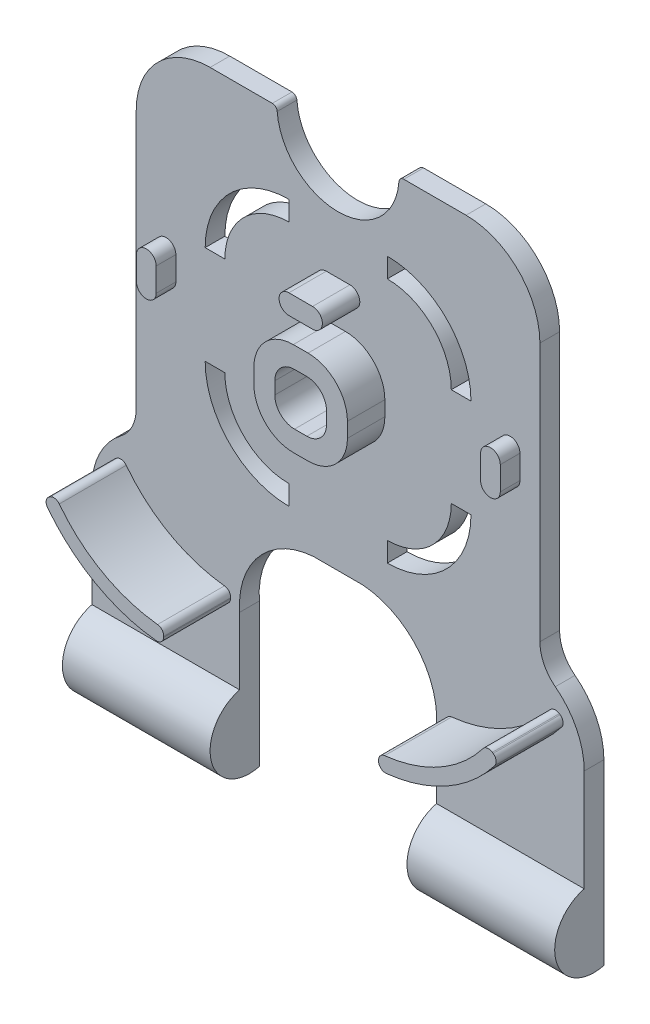
SolidWorks part; units mm, degrees
ref_plane "Front Plane" through (0, 0, 0) normal (0, 0, 1) x (1, 0, 0)
ref_plane "Top Plane" through (0, 0, 0) normal (0, 1, 0) x (1, 0, 0)
ref_plane "Right Plane" through (0, 0, 0) normal (1, 0, 0) x (0, 0, -1)
sketch "Sketch5" plane through (0, 0, 0) normal (0, 0, 1) x (1, 0, 0)
  line L0 (24, 16.7992) -> (36.6374, 16.7992)
  line L1 (91, 1.7992) -> (91, -50.7428)
  line L5 (55, -58.7428) -> (45, -58.7428)
  line L10 (9, -50.7428) -> (9, 1.7992)
  line L11 (23, -35.4056) -> (27, -35.4056)
  line L12 (40, -48.4056) -> (40, -52.4056)
  line L13 (60, -48.4056) -> (60, -52.4056)
  line L14 (73, -35.4056) -> (77, -35.4056)
  line L15 (0, -97.4535) -> (30, -97.4535)
  line L16 (24.5379, -25.4056) -> (75.4621, -25.4056) construction
  line L17 (50, -50.8112) -> (50, 0) construction
  line L18 (73, -15.4056) -> (77, -15.4056)
  line L19 (60, -2.4056) -> (60, 1.5944)
  line L20 (40, -2.4056) -> (40, 1.5944)
  line L21 (23, -15.4056) -> (27, -15.4056)
  line L22 (48.75, -20.1556) -> (51.25, -20.1556)
  line L23 (55.25, -24.1556) -> (55.25, -26.6556)
  line L24 (51.25, -30.6556) -> (48.75, -30.6556)
  line L25 (44.75, -26.6556) -> (44.75, -24.1556)
  line L31 (47.613, -7.2456) -> (52.413, -7.2456)
  line L32 (52.413, -11.2456) -> (47.613, -11.2456)
  line L41 (30, -76.0634) -> (30, -97.4535)
  line L42 (0, -68.9911) -> (0, -97.4535)
  line L43 (70, -76.0634) -> (70, -97.4535)
  line L44 (70, -97.4535) -> (100, -97.4535)
  line L45 (100, -97.4535) -> (100, -68.9911)
  line L46 (63.3626, 16.7992) -> (76, 16.7992)
  arc A0 (76, 16.7992) -> (91, 1.7992) centre (76, 1.7992) cw
  arc A1 (91, -50.7428) -> (94.1304, -57.0901) centre (99, -50.7428) ccw
  arc A2 (94.1304, -57.0901) -> (100, -68.9911) centre (85, -68.9911) cw
  arc A3 (0, -68.9911) -> (5.8696, -57.0901) centre (15, -68.9911) cw
  arc A4 (5.8696, -57.0901) -> (9, -50.7428) centre (1, -50.7428) ccw
  arc A5 (9, 1.7992) -> (24, 16.7992) centre (24, 1.7992) cw
  arc A6 (37.6346, 15.8738) -> (62.3654, 15.8738) centre (50, 16.7992) ccw
  arc A7 (37.6346, 15.8738) -> (36.6374, 16.7992) centre (36.6374, 15.7992) ccw
  arc A8 (27, -35.4056) -> (40, -48.4056) centre (40, -35.4056) ccw
  arc A9 (23, -35.4056) -> (40, -52.4056) centre (40, -35.4056) ccw
  arc A10 (77, -35.4056) -> (60, -52.4056) centre (60, -35.4056) cw
  arc A11 (73, -35.4056) -> (60, -48.4056) centre (60, -35.4056) cw
  arc A12 (73, -15.4056) -> (60, -2.4056) centre (60, -15.4056) ccw
  arc A13 (77, -15.4056) -> (60, 1.5944) centre (60, -15.4056) ccw
  arc A14 (23, -15.4056) -> (40, 1.5944) centre (40, -15.4056) cw
  arc A15 (27, -15.4056) -> (40, -2.4056) centre (40, -15.4056) cw
  arc A16 (45, -58.7428) -> (30, -76.0634) centre (46.1603, -74.9031) ccw
  arc A17 (55, -58.7428) -> (70, -76.0634) centre (53.8397, -74.9031) cw
  arc A18 (62.3654, 15.8738) -> (63.3626, 16.7992) centre (63.3626, 15.7992) cw
  arc A19 (44.75, -24.1556) -> (48.75, -20.1556) centre (48.75, -24.1556) cw
  arc A20 (51.25, -20.1556) -> (55.25, -24.1556) centre (51.25, -24.1556) cw
  arc A21 (55.25, -26.6556) -> (51.25, -30.6556) centre (51.25, -26.6556) cw
  arc A22 (44.75, -26.6556) -> (48.75, -30.6556) centre (48.75, -26.6556) ccw
  arc A28 (47.613, -7.2456) -> (47.613, -11.2456) centre (47.613, -9.2456) ccw
  arc A29 (52.413, -7.2456) -> (52.413, -11.2456) centre (52.413, -9.2456) cw
  point P23 (62.4, 16.7992)
  point P98 (50, -25.4056)
  point P112 (50, -25.4056)
  dimension "D1" = 1
  dimension "D2" = 1
sketch "Sketch6" plane through (0, 0, 0) normal (0, 0, 1) x (1, 0, 0)
  line L0 (13.05, -19.6056) -> (13.05, -24.4056)
  line L1 (17.05, -19.6056) -> (17.05, -24.4056)
  line L2 (82.95, -19.6056) -> (82.95, -24.4056)
  line L3 (86.95, -19.6056) -> (86.95, -24.4056)
  arc A0 (13.05, -19.6056) -> (17.05, -19.6056) centre (15.05, -19.6056) cw
  arc A1 (82.95, -19.6056) -> (86.95, -19.6056) centre (84.95, -19.6056) cw
  arc A2 (13.05, -24.4056) -> (17.05, -24.4056) centre (15.05, -24.4056) ccw
  arc A3 (82.95, -24.4056) -> (86.95, -24.4056) centre (84.95, -24.4056) ccw
sketch "Sketch7" plane through (0, 0, 0) normal (0, 0, 1) x (1, 0, 0)
  line L0 (40.5, -23.9056) -> (40.5, -26.9056)
  line L1 (48.5, -15.9056) -> (51.5, -15.9056)
  line L2 (59.5, -23.9056) -> (59.5, -26.9056)
  line L3 (51.5, -34.9056) -> (48.5, -34.9056)
  line L4 (47.613, -11.2456) -> (52.413, -11.2456)
  line L5 (52.413, -7.2456) -> (47.613, -7.2456)
  line L6 (44.75, -24.1556) -> (44.75, -26.6556)
  line L7 (55.25, -24.1556) -> (55.25, -26.6556)
  line L8 (51.25, -30.6556) -> (48.75, -30.6556)
  line L9 (51.25, -20.1556) -> (48.75, -20.1556)
  arc A0 (52.413, -7.2456) -> (52.413, -11.2456) centre (52.413, -9.2456) cw
  arc A1 (47.613, -7.2456) -> (47.613, -11.2456) centre (47.613, -9.2456) ccw
  arc A2 (51.5, -15.9056) -> (59.5, -23.9056) centre (51.5, -23.9056) cw
  arc A3 (48.5, -15.9056) -> (40.5, -23.9056) centre (48.5, -23.9056) ccw
  arc A4 (40.5, -26.9056) -> (48.5, -34.9056) centre (48.5, -26.9056) ccw
  arc A5 (59.5, -26.9056) -> (51.5, -34.9056) centre (51.5, -26.9056) cw
  arc A6 (51.25, -20.1556) -> (55.25, -24.1556) centre (51.25, -24.1556) cw
  arc A7 (55.25, -26.6556) -> (51.25, -30.6556) centre (51.25, -26.6556) cw
  arc A8 (48.75, -30.6556) -> (44.75, -26.6556) centre (48.75, -26.6556) cw
  arc A9 (44.75, -24.1556) -> (48.75, -20.1556) centre (48.75, -24.1556) cw
sketch "Sketch8" plane through (0, 0, 0) normal (0, 0, 1) x (1, 0, 0)
  line L0 (5.052, -61.4202) -> (4.8891, -61.5332)
  line L1 (28.1754, -74.4185) -> (28.1635, -74.6163)
  line L3 (71.8246, -74.4185) -> (71.8365, -74.6163)
  line L4 (94.948, -61.4202) -> (95.1109, -61.5332)
  arc A2 (6.9623, -61.72) -> (26.9263, -72.9422) centre (30, -44.1056) ccw
  arc A4 (4.5761, -63.5349) -> (26.6161, -75.9242) centre (30.0517, -44.0137) ccw
  arc A5 (4.8891, -61.5332) -> (4.5761, -63.5349) centre (5.6873, -62.6833) ccw
  arc A6 (5.052, -61.4202) -> (6.9623, -61.72) centre (5.8502, -62.5703) cw
  arc A7 (28.1635, -74.6163) -> (26.6161, -75.9242) centre (26.766, -74.5322) cw
  arc A8 (28.1754, -74.4185) -> (26.9263, -72.9422) centre (26.7779, -74.3343) ccw
  arc A9 (71.8246, -74.4185) -> (73.0737, -72.9422) centre (73.2221, -74.3343) cw
  arc A10 (71.8365, -74.6163) -> (73.3839, -75.9242) centre (73.234, -74.5322) ccw
  arc A11 (94.948, -61.4202) -> (93.0377, -61.72) centre (94.1498, -62.5703) ccw
  arc A12 (95.1109, -61.5332) -> (95.4239, -63.5349) centre (94.3127, -62.6833) cw
  arc A13 (95.4239, -63.5349) -> (73.3839, -75.9242) centre (69.9483, -44.0137) cw
  arc A14 (93.0377, -61.72) -> (73.0737, -72.9422) centre (70, -44.1056) cw
  point P9 (0, 0)
  point P17 (0, 0)
  point P19 (0, 0)
  point P20 (0, 0)
  point P21 (50, -66.2535)
  dimension "D1" = 1.4
extrude "Boss-Extrude1" add sketch "Sketch5" against normal blind 4
sketch "Sketch9" plane through (100, 0, 0) normal (1, 0, 0) x (0, 0, -1)
  line L0 (4, -97.4535) -> (0, -97.4535) construction
  line L1 (0, -89.7075) -> (0, -97.4535)
  line L2 (0, -97.4535) -> (4, -97.4535)
  line L3 (4, -97.4535) -> (4, -105.1994)
  arc A0 (0, -89.7075) -> (4, -105.1994) centre (2, -97.4535) ccw
extrude "Boss-Extrude5" add sketch "Sketch9" against normal blind 100
sketch "Sketch10" plane through (0, 0, 0) normal (0, 0, 1) x (1, 0, 0)
  line L0 (30, -89.7075) -> (30, -105.4535)
  line L1 (0, -105.4535) -> (100, -105.4535) construction
  line L2 (30, -105.4535) -> (70, -105.4535)
  line L3 (70, -105.4535) -> (70, -89.7075)
  line L4 (70, -89.7075) -> (30, -89.7075)
extrude "Cut-Extrude1" cut sketch "Sketch10" against normal blind 4 and the other way blind 6
extrude "Boss-Extrude2" add sketch "Sketch7" along normal blind 7.6
extrude "Boss-Extrude3" add sketch "Sketch6" along normal blind 4
extrude "Boss-Extrude4" add sketch "Sketch8" along normal blind 13.6
